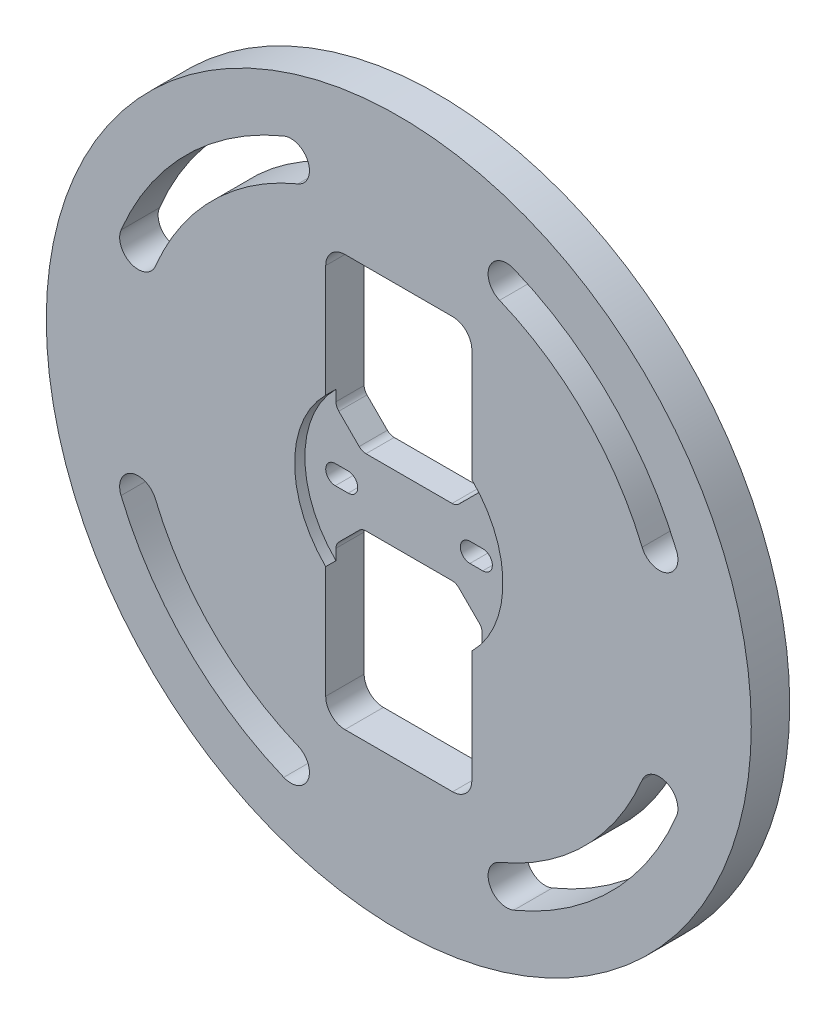
SolidWorks part; units mm, degrees
material "ABS"
ref_plane "Front Plane" through (0, 0, 0) normal (0, 0, 1) x (1, 0, 0)
ref_plane "Top Plane" through (0, 0, 0) normal (0, 1, 0) x (1, 0, 0)
ref_plane "Right Plane" through (0, 0, 0) normal (1, 0, 0) x (0, 0, -1)
sketch "Sketch1" plane through (0, 0, 0) normal (0, 0, 1) x (1, 0, 0)
  circle A0 centre (0, 0) radius 55
  dimension "D1" = 110
extrude "Boss-Extrude1" add sketch "Sketch1" along normal blind 6
sketch "Sketch3" plane through (0, 0, 6) normal (0, 0, 1) x (1, 0, 0)
  arc A75 (-15.7283, 37.9714) -> (-17.9479, 43.33) centre (-16.8381, 40.6507) ccw
  arc A77 (17.9479, 43.33) -> (15.7283, 37.9714) centre (16.8381, 40.6507) ccw
  arc A79 (37.9714, 15.7283) -> (43.33, 17.9479) centre (40.6507, 16.8381) ccw
  arc A81 (43.33, -17.9479) -> (37.9714, -15.7283) centre (40.6507, -16.8381) ccw
  arc A83 (15.7283, -37.9714) -> (17.9479, -43.33) centre (16.8381, -40.6507) ccw
  arc A85 (-17.9479, -43.33) -> (-15.7283, -37.9714) centre (-16.8381, -40.6507) ccw
  arc A87 (-37.9714, -15.7283) -> (-43.33, -17.9479) centre (-40.6507, -16.8381) ccw
  arc A89 (-43.33, 17.9479) -> (-37.9714, 15.7283) centre (-40.6507, 16.8381) ccw
  arc A91 (-43.33, -17.9479) -> (-17.9479, -43.33) centre (0, 0) ccw
  arc A92 (-37.9714, -15.7283) -> (-15.7283, -37.9714) centre (0, 0) ccw
  arc A93 (-17.9479, 43.33) -> (-43.33, 17.9479) centre (0, 0) ccw
  arc A94 (-15.7283, 37.9714) -> (-37.9714, 15.7283) centre (0, 0) ccw
  arc A95 (37.9714, 15.7283) -> (15.7283, 37.9714) centre (0, 0) ccw
  arc A96 (43.33, 17.9479) -> (17.9479, 43.33) centre (0, 0) ccw
  arc A97 (15.7283, -37.9714) -> (37.9714, -15.7283) centre (0, 0) ccw
  arc A98 (17.9479, -43.33) -> (43.33, -17.9479) centre (0, 0) ccw
extrude "Cut-Extrude1" cut sketch "Sketch3" against normal through all
sketch "Sketch4" plane through (0, 0, 6) normal (0, 0, 1) x (1, 0, 0)
  circle A0 centre (0, 0) radius 16.25
  dimension "D1" = 32.5
extrude "Cut-Extrude2" cut sketch "Sketch4" against normal blind 1.6
sketch "Sketch5" plane through (0, 0, 4.4) normal (0, 0, 1) x (1, 0, 0)
  line L0 (0, 0) -> (-11.5, 0) construction
  line L1 (0, 0) -> (-6.7175, -6.7175) construction
  line L2 (-6.7175, -6.7175) -> (-9.8995, -9.8995) construction
  line L3 (-5.6569, -7.7782) -> (-8.8388, -10.9602)
  line L4 (-7.7782, -5.6569) -> (-10.9602, -8.8388)
  line L5 (-9.5, 0) -> (-11.5, 0) construction
  line L6 (-9.5, -1.5) -> (-11.5, -1.5)
  line L7 (-9.5, 1.5) -> (-11.5, 1.5)
  line L8 (-6.7175, 6.7175) -> (-9.8995, 9.8995) construction
  line L9 (-7.7782, 5.6569) -> (-10.9602, 8.8388)
  line L10 (-5.6569, 7.7782) -> (-8.8388, 10.9602)
  line L11 (6.7175, 6.7175) -> (9.8995, 9.8995) construction
  line L12 (5.6569, 7.7782) -> (8.8388, 10.9602)
  line L13 (7.7782, 5.6569) -> (10.9602, 8.8388)
  line L14 (6.7175, -6.7175) -> (9.8995, -9.8995) construction
  line L15 (7.7782, -5.6569) -> (10.9602, -8.8388)
  line L16 (5.6569, -7.7782) -> (8.8388, -10.9602)
  line L17 (9.5, 0) -> (11.5, 0) construction
  line L18 (9.5, 1.5) -> (11.5, 1.5)
  line L19 (9.5, -1.5) -> (11.5, -1.5)
  arc A0 (-5.6569, -7.7782) -> (-7.7782, -5.6569) centre (-6.7175, -6.7175) ccw
  arc A1 (-10.9602, -8.8388) -> (-8.8388, -10.9602) centre (-9.8995, -9.8995) ccw
  arc A2 (-9.5, -1.5) -> (-9.5, 1.5) centre (-9.5, 0) ccw
  arc A3 (-11.5, 1.5) -> (-11.5, -1.5) centre (-11.5, 0) ccw
  arc A4 (-7.7782, 5.6569) -> (-5.6569, 7.7782) centre (-6.7175, 6.7175) ccw
  arc A5 (-8.8388, 10.9602) -> (-10.9602, 8.8388) centre (-9.8995, 9.8995) ccw
  arc A6 (5.6569, 7.7782) -> (7.7782, 5.6569) centre (6.7175, 6.7175) ccw
  arc A7 (10.9602, 8.8388) -> (8.8388, 10.9602) centre (9.8995, 9.8995) ccw
  arc A8 (7.7782, -5.6569) -> (5.6569, -7.7782) centre (6.7175, -6.7175) ccw
  arc A9 (8.8388, -10.9602) -> (10.9602, -8.8388) centre (9.8995, -9.8995) ccw
  arc A10 (9.5, 1.5) -> (9.5, -1.5) centre (9.5, 0) ccw
  arc A11 (11.5, -1.5) -> (11.5, 1.5) centre (11.5, 0) ccw
  point P2 (-8.3085, -8.3085)
  point P11 (-10.5, 0)
  point P16 (0, 0)
  point P18 (-8.3085, 8.3085)
  point P25 (8.3085, 8.3085)
  point P32 (8.3085, -8.3085)
  point P39 (0, 0)
  point P41 (10.5, 0)
  point P46 (0, 0)
  dimension "D1" = 1.5
  dimension "D3" = 1.5
  dimension "D2" = 4.5
  dimension "D4" = 2
extrude "Cut-Extrude3" cut sketch "Sketch5" against normal through all
sketch "Sketch6" plane through (0, 0, 4.4) normal (0, 0, 1) x (1, 0, 0)
  line L0 (0, 5.2175) -> (0, 0) construction
  line L5 (-8.3995, -32.1005) -> (8.3995, -32.1005)
  line L19 (8.3995, 32.1005) -> (-8.3995, 32.1005)
  line L21 (11.3995, 29.1005) -> (11.3995, 9.8995)
  line L23 (-11.3995, 29.1005) -> (-11.3995, 9.8995)
  line L24 (-11.3995, 9.8995) -> (-6.7175, 5.2175)
  line L25 (11.3995, 9.8995) -> (6.7175, 5.2175)
  line L27 (6.7175, 5.2175) -> (-6.7175, 5.2175)
  line L29 (-11.3995, -29.1005) -> (-11.3995, -9.8995)
  line L30 (11.3995, -29.1005) -> (11.3995, -9.8995)
  line L32 (11.3995, -9.8995) -> (6.7175, -5.2175)
  line L34 (-11.3995, -9.8995) -> (-6.7175, -5.2175)
  line L35 (-6.7175, -5.2175) -> (6.7175, -5.2175)
  line L36 (0, 0) -> (0, -5.2175) construction
  arc A0 (-8.8388, 10.9602) -> (-10.9602, 8.8388) centre (-9.8995, 9.8995) ccw construction
  arc A1 (-7.7782, 5.6569) -> (-5.6569, 7.7782) centre (-6.7175, 6.7175) ccw construction
  arc A2 (-8.3995, -32.1005) -> (-11.3995, -29.1005) centre (-8.3995, -29.1005) cw
  arc A3 (8.3995, -32.1005) -> (11.3995, -29.1005) centre (8.3995, -29.1005) ccw
  arc A4 (11.3995, 29.1005) -> (8.3995, 32.1005) centre (8.3995, 29.1005) ccw
  arc A5 (-11.3995, 29.1005) -> (-8.3995, 32.1005) centre (-8.3995, 29.1005) cw
  dimension "D3" = 3
  dimension "D1" = 5.2175
  dimension "D2" = 5.2175
extrude "Cut-Extrude4" cut sketch "Sketch6" against normal through all both and the other way through all
